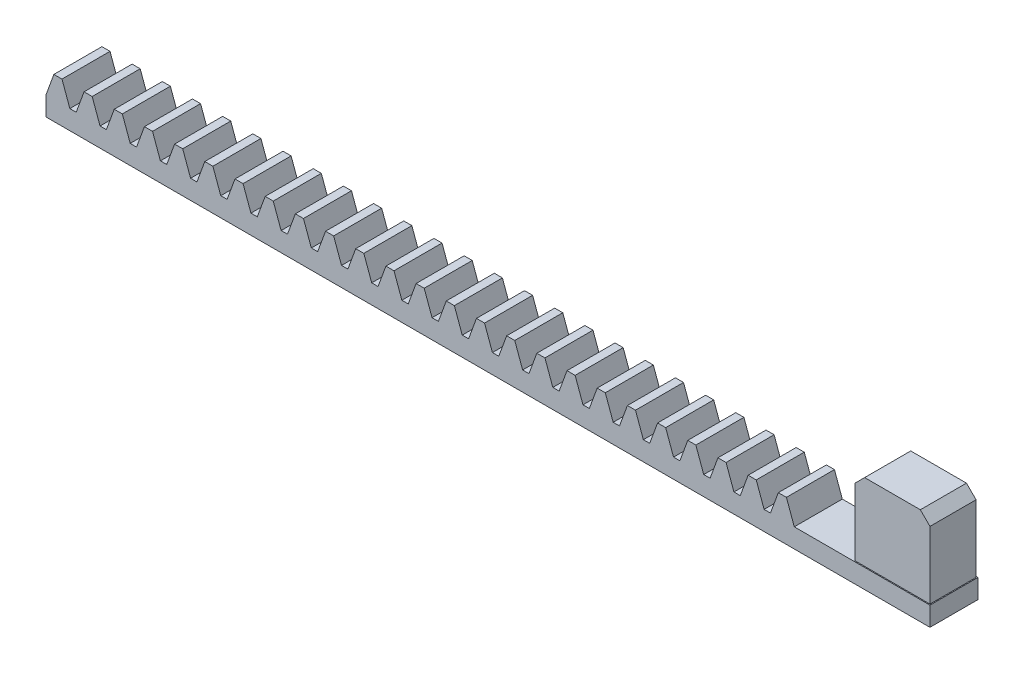
SolidWorks part; units mm, degrees
ref_plane "前视基准面" through (0, 0, 0) normal (0, 0, 1) x (1, 0, 0)
ref_plane "上视基准面" through (0, 0, 0) normal (0, 1, 0) x (1, 0, 0)
ref_plane "右视基准面" through (0, 0, 0) normal (1, 0, 0) x (0, 0, -1)
sketch "草图1" plane through (0, 0, 0) normal (0, 0, 1) x (1, 0, 0)
  line L1 (0, 0) -> (80, 0)
  line L2 (0, 0) -> (0, -10)
  line L3 (0, -10) -> (80, -10)
  line L4 (80, 0) -> (80, -10)
  dimension "D1" = 10
  dimension "L" = 80
extrude "拉伸1" add sketch "草图1" along normal blind 5
sketch "草图2" plane through (0, 0, 5) normal (0, 0, 1) x (1, 0, 0)
  line L0 (0, 0) -> (0.8189, 2.25)
  line L1 (0.8189, 2.25) -> (1.6618, 2.25)
  line L2 (1.6618, 2.25) -> (2.4807, 0)
  line L3 (80, 0) -> (0, 0) construction
  line L4 (0, 0) -> (2.4807, 0)
  line L5 (0.455, 1.25) -> (2.0258, 1.25) construction
  dimension "D2" = 70
  dimension "alpha" = 110
  dimension "ha" = 1
  dimension "hf" = 1.25
  dimension "S" = 1.5708
extrude "拉伸2" add sketch "草图2" against normal up to surface (5 mm away) up to face at (40, -5, 0)
pattern_linear "阵列(线性)1" count 25 spacing 3.1416 along (1, 0, 0) of "拉伸2"
sketch "草图3" plane through (0, 0, 5) normal (0, 0, 1) x (1, 0, 0)
  line L0 (0, 0) -> (0, -10) construction
  line L1 (0, -2) -> (80, -2)
  line L2 (0, -2) -> (0, -10)
  line L3 (0, -10) -> (80, -10)
  line L4 (80, -2) -> (80, -10)
  dimension "D1" = 8
extrude "切除-拉伸1" cut sketch "草图3" against normal blind 10
sketch "草图4" plane through (0, 0, 5) normal (0, 0, 1) x (1, 0, 0)
  line L1 (80, 0) -> (84, 0)
  line L2 (80, 0) -> (80, -2)
  line L3 (80, -2) -> (92, -2)
  line L4 (92, 0) -> (92, -2)
  line L6 (92, 0) -> (92, 8)
  line L7 (92, 8) -> (84, 8)
  line L8 (84, 0) -> (84, 8)
  dimension "D1" = 2
  dimension "D2" = 12
  dimension "D3" = 8
  dimension "D4" = 8
  dimension "D5" = 4
  dimension "D6" = 2
extrude "凸台-拉伸1" add sketch "草图4" against normal blind 5
sketch "草图5" plane through (0, 8, 0) normal (0, 1, 0) x (1, 0, 0)
  line L0 (84.1, -4.9) -> (91.9, -4.9)
  line L1 (91.9, -4.9) -> (91.9, -0.1)
  line L2 (91.9, -0.1) -> (84.1, -0.1)
  line L3 (84.1, -0.1) -> (84.1, -4.9)
  line L4 (84, -5) -> (92, -5)
  line L5 (92, -5) -> (92, 0)
  line L6 (92, 0) -> (84, 0)
  line L7 (84, 0) -> (84, -5)
  line L8 (84, -5) -> (92, -5)
  line L9 (92, -5) -> (92, 0)
  line L10 (92, 0) -> (84, 0)
  line L11 (84, 0) -> (84, -5)
  dimension "D1" = 0
  dimension "D2" = 0.1
extrude "切除-拉伸3" cut sketch "草图5" against normal blind 8
chamfer "倒角1" distance 1 angle 45 2 edges at (84.1, 8, 2.5) (91.9, 8, 2.5)
equation "\"D2@草图2\" = 180 - \"alpha@草图2\""
equation "\"d\"=\"S@草图2\" * 2"
equation "\"z\"= int(  \"L@草图1\" / (  \"S@草图2\" * 2 ) + 0.5 )"
